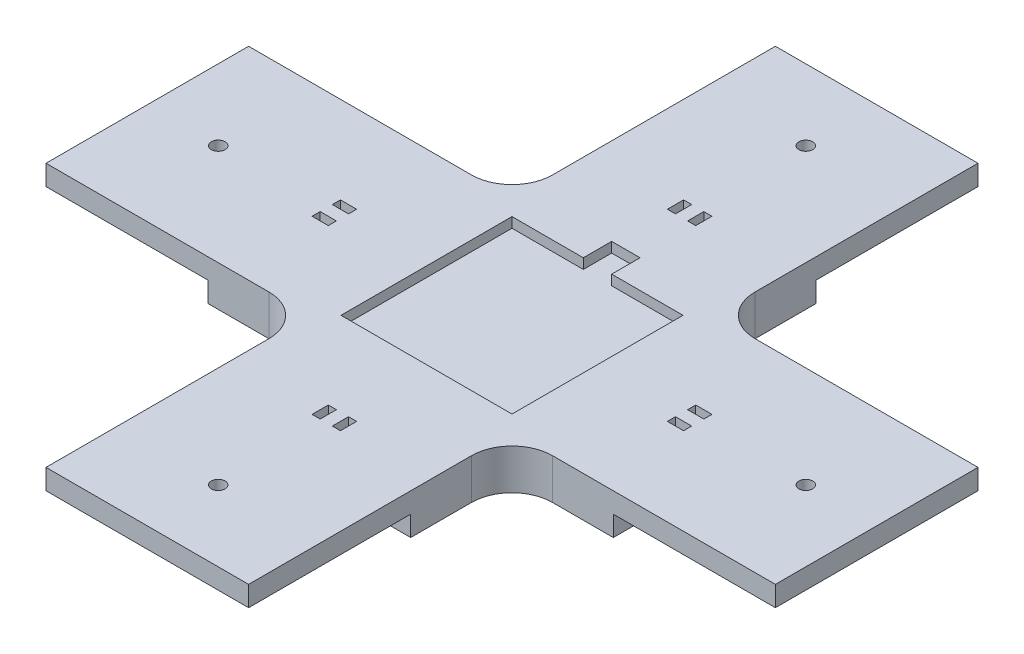
SolidWorks part; units mm, degrees
ref_plane "Płaszczyzna przednia" through (0, 0, 0) normal (0, 0, 1) x (1, 0, 0)
ref_plane "Płaszczyzna górna" through (0, 0, 0) normal (0, 1, 0) x (1, 0, 0)
ref_plane "Płaszczyzna prawa" through (0, 0, 0) normal (1, 0, 0) x (0, 0, -1)
sketch "Sketch2" plane through (0, 0, 0) normal (0, 0, 1) x (1, 0, 0)
  line L0 (-50, 0) -> (50, 0)
  line L1 (-50, 0) -> (-50, 5)
  line L2 (-50, 5) -> (-90, 5)
  line L3 (-90, 5) -> (-90, 10)
  line L4 (-90, 10) -> (90, 10)
  line L5 (50, 0) -> (50, 5)
  line L6 (50, 5) -> (90, 5)
  line L7 (90, 5) -> (90, 10)
  point P3 (0, 0)
  point P10 (0, 10)
  dimension "D1" = 5
  dimension "D2" = 40
  dimension "D3" = 100
  dimension "D4" = 5
extrude "Boss-Extrude2" add sketch "Sketch2" along normal mid plane 50
sketch "Sketch4" plane through (0, 10, 0) normal (0, 1, 0) x (1, 0, 0)
  line L0 (-3.5, 21.1) -> (-21.1, 21.1)
  line L1 (21.1, -21.1) -> (-21.1, -21.1)
  line L2 (21.1, -21.1) -> (21.1, 21.1)
  line L3 (21.1, 21.1) -> (3.5, 21.1)
  line L4 (-21.1, -21.1) -> (-21.1, 21.1)
  line L5 (21.1, -21.1) -> (-21.1, 21.1) construction
  line L6 (21.1, 21.1) -> (-21.1, -21.1) construction
  line L8 (-3.5, 21.1) -> (-3.5, 28.1)
  line L9 (-3.5, 28.1) -> (3.5, 28.1)
  line L10 (3.5, 21.1) -> (3.5, 28.1)
  point P0 (0, 0)
  point P6 (0, 21)
  point P10 (0, 28.1)
  dimension "D2" = 7
  dimension "D3" = 7
  dimension "D4" = 42.2
sketch "Sketch7" plane through (0, 0, 0) normal (0, 0, 1) x (1, 0, 0)
  line L0 (0, 0) -> (0, 72.6994) construction
pattern_circular "CirPattern2" count 4 over 360 about axis through (0, 0, 0) along (0, 1, 0) of "Boss-Extrude2"
extrude "Cut-Extrude2" cut sketch "Sketch4" against normal mid plane 5
fillet "Fillet1" radius 10 4 edges at (25, 5, 25) (-25, 5, 25) (25, 5, -25) (-25, 5, -25)
sketch "Sketch8" plane through (0, 10, 0) normal (0, 1, 0) x (1, 0, 0)
  circle A0 centre (-72.5, 0) radius 1.7
extrude "Cut-Extrude3" cut sketch "Sketch8" against normal through all
pattern_circular "CirPattern3" count 4 over 360 about axis through (0, 0, 0) along (0, 1, 0) of "Cut-Extrude3"
sketch "Sketch9" plane through (0, 10, 0) normal (0, 1, 0) x (1, 0, 0)
  line L0 (-43.8406, 0) -> (0, 43.8406) construction
  line L1 (-43.8406, 0) -> (0, -43.8406) construction
  line L2 (0, 43.8406) -> (43.8406, 0) construction
  line L3 (0, -43.8406) -> (43.8406, 0) construction
  line L4 (-43.8406, 0) -> (43.8406, 0) construction
  line L5 (0, 43.8406) -> (0, -43.8406) construction
  point P1 (0, 0)
  dimension "D1" = 62
sketch "Sketch10" plane through (0, 10, 0) normal (0, 1, 0) x (1, 0, 0)
  line L0 (-43.8406, -2.5) -> (-43.8406, 2.5) construction
  line L3 (-46.2951, 0) -> (-41.1346, 0) construction
  line L4 (-45.8406, 3.5) -> (-41.8406, 3.5)
  line L5 (-45.8406, 3.5) -> (-45.8406, 1.5)
  line L6 (-45.8406, 1.5) -> (-41.8406, 1.5)
  line L7 (-41.8406, 3.5) -> (-41.8406, 1.5)
  line L8 (-45.8406, 3.5) -> (-41.8406, 1.5) construction
  line L9 (-45.8406, 1.5) -> (-41.8406, 3.5) construction
  line L10 (-43.8406, 0) -> (43.8406, 0) construction
  line L11 (-45.8406, -1.5) -> (-41.8406, -3.5) construction
  line L12 (-45.8406, -3.5) -> (-41.8406, -1.5) construction
  line L13 (-41.8406, -3.5) -> (-41.8406, -1.5)
  line L14 (-45.8406, -1.5) -> (-41.8406, -1.5)
  line L15 (-45.8406, -3.5) -> (-45.8406, -1.5)
  line L16 (-45.8406, -3.5) -> (-41.8406, -3.5)
  point P4 (-43.8406, 0)
  dimension "D1" = 4
  dimension "D2" = 2
  dimension "D3" = 5
extrude "Cut-Extrude4" cut sketch "Sketch10" against normal through all
sketch "Sketch11" plane through (0, 0, 0) normal (0, -1, 0) x (1, 0, 0)
  line L1 (-47.8406, -5) -> (-39.8406, -5)
  line L2 (-47.8406, -5) -> (-47.8406, 5)
  line L3 (-47.8406, 5) -> (-39.8406, 5)
  line L4 (-39.8406, -5) -> (-39.8406, 5)
  line L5 (-47.8406, -5) -> (-39.8406, 5) construction
  line L6 (-47.8406, 5) -> (-39.8406, -5) construction
  point P0 (-43.8406, 0)
  dimension "D1" = 8
  dimension "D2" = 10
extrude "Cut-Extrude5" cut sketch "Sketch11" against normal offset from surface (7 mm away) 3 up to face at (-43.8406, 10, -2.5)
pattern_circular "CirPattern4" count 4 over 360 about axis through (0, 0, 0) along (0, 1, 0) of "Cut-Extrude5", "Cut-Extrude4"
